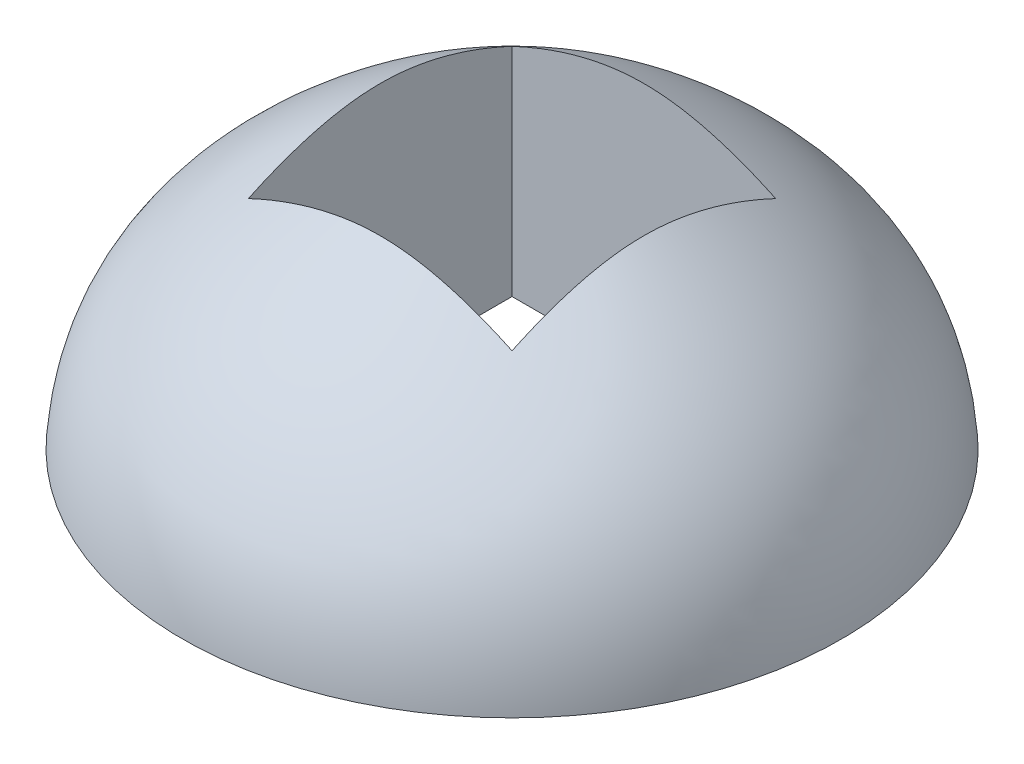
SolidWorks part; units mm, degrees
ref_plane "Front Plane" through (0, 0, 0) normal (0, 0, 1) x (1, 0, 0)
ref_plane "Top Plane" through (0, 0, 0) normal (0, 1, 0) x (1, 0, 0)
ref_plane "Right Plane" through (0, 0, 0) normal (1, 0, 0) x (0, 0, -1)
sketch "Sketch1" plane through (0, 0, 0) normal (0, 0, 1) x (1, 0, 0)
  line L0 (0, 0) -> (0, 0.5)
  line L1 (0, 0) -> (0.5, 0)
  spline S0 degree 3 poles (0.5, 0) (0.4803, 0.2853) (0.196, 0.3626) (0, 0.5) knots 0 0 0 0 1 1 1 1
  point P5 (0.1029, 0.4356)
  point P7 (0.4033, 0.228)
  dimension "D1" = 0.5
  dimension "D2" = 0.5
revolve "Revolve1" add sketch "Sketch1" angle 360 about L0
sketch "Sketch2" plane through (0, 0, 0) normal (0, -1, 0) x (1, 0, 0)
  line L1 (-0.2, -0.2) -> (0.2, -0.2)
  line L2 (-0.2, -0.2) -> (-0.2, 0.2)
  line L3 (-0.2, 0.2) -> (0.2, 0.2)
  line L4 (0.2, -0.2) -> (0.2, 0.2)
  line L5 (-0.2, -0.2) -> (0.2, 0.2) construction
  line L6 (-0.2, 0.2) -> (0.2, -0.2) construction
  point P0 (0, 0)
  dimension "D1" = 0.4
extrude "Cut-Extrude1" cut sketch "Sketch2" against normal through all
